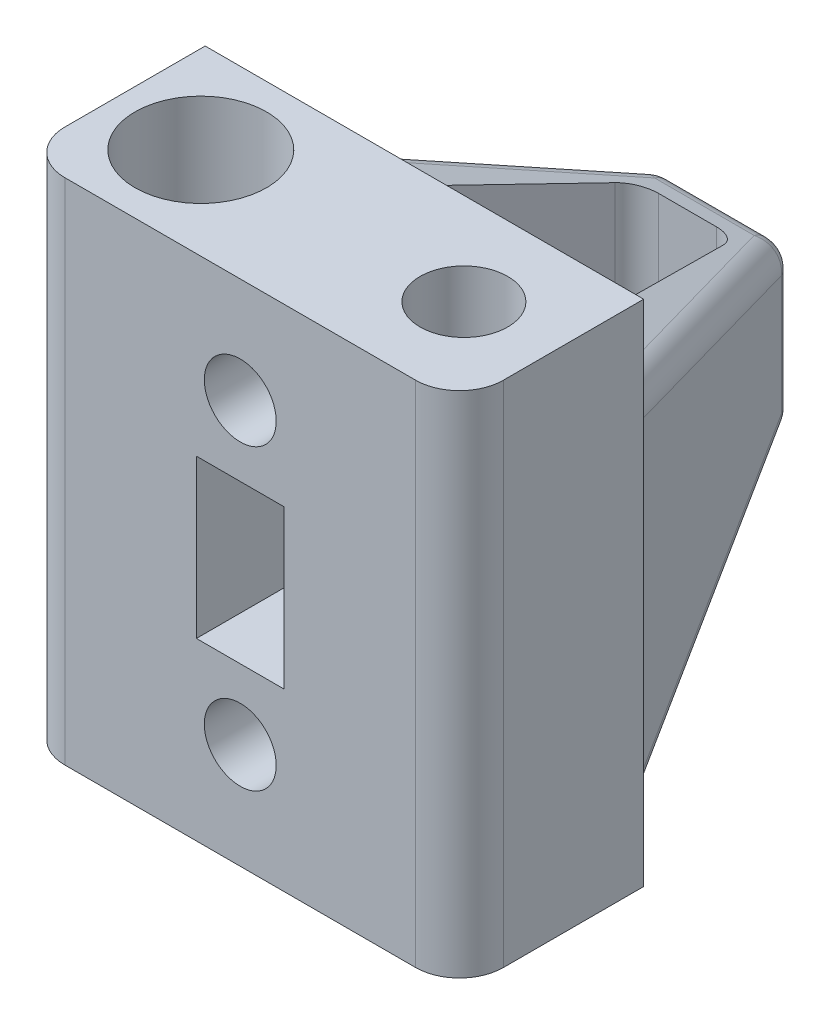
SolidWorks part; units mm, degrees
ref_plane "Front Plane" through (0, 0, 0) normal (0, 0, 1) x (1, 0, 0)
ref_plane "Top Plane" through (0, 0, 0) normal (0, 1, 0) x (1, 0, 0)
ref_plane "Right Plane" through (0, 0, 0) normal (1, 0, 0) x (0, 0, -1)
sketch "Sketch1" plane through (0, 0, 0) normal (0, 1, 0) x (1, 0, 0)
  line L1 (-25, 10.5) -> (25, 10.5)
  line L2 (-25, 10.5) -> (-25, -10.5)
  line L3 (-25, -10.5) -> (25, -10.5)
  line L4 (25, 10.5) -> (25, -10.5)
  line L5 (-25, 10.5) -> (25, -10.5) construction
  line L6 (-25, -10.5) -> (25, 10.5) construction
  point P0 (0, 0)
  dimension "D1" = 21
  dimension "D2" = 50
extrude "Boss-Extrude1" add sketch "Sketch1" along normal blind 58
sketch "Sketch3" plane through (0, 58, 0) normal (0, 1, 0) x (1, 0, 0)
  line L0 (-15, 0) -> (15, 0) construction
  circle A0 centre (-15, 0) radius 7.5
  dimension "D1" = 15
  dimension "D2" = 30
extrude "Cut-Extrude1" cut sketch "Sketch3" against normal blind 24 contours A0
sketch "Sketch4" plane through (0, 58, 0) normal (0, 1, 0) x (1, 0, 0)
  line L0 (-15, 0) -> (15, 0) construction
  circle A0 centre (15, 0) radius 5
  dimension "D1" = 10
extrude "Cut-Extrude2" cut sketch "Sketch4" against normal up to next
sketch "Sketch5" plane through (0, 0, 0) normal (0, -1, 0) x (1, 0, 0)
  circle A1 centre (-15, 0) radius 7.5
  circle A2 centre (-15, 0) radius 7.5
  dimension "D1" = 0
extrude "Cut-Extrude3" cut sketch "Sketch5" against normal blind 24
sketch "Sketch6" plane through (0, 0, 0) normal (0, -1, 0) x (1, 0, 0)
  circle A0 centre (-15, 0) radius 4.5
extrude "Cut-Extrude4" cut sketch "Sketch6" against normal up to next
sketch "Sketch7" plane through (0, 0, 10.5) normal (0, 0, 1) x (1, 0, 0)
  line L0 (0, 58) -> (0, 0) construction
  line L1 (-25, 58) -> (25, 58) construction
  line L2 (-25, 0) -> (25, 0) construction
  line L3 (-25, 29) -> (25, 29) construction
  line L4 (-25, 58) -> (-25, 0) construction
  line L5 (25, 58) -> (25, 0) construction
  circle A1 centre (0, 46) radius 4.1
  circle A2 centre (0, 12) radius 4.1
  point P24 (0, 12)
  dimension "D1" = 8.2
  dimension "D2" = 12
sketch "Sketch8" plane through (0, 0, 10.5) normal (0, 0, 1) x (1, 0, 0)
  line L0 (-25, 29) -> (25, 29) construction
  line L1 (-25, 58) -> (-25, 0) construction
  line L2 (25, 58) -> (25, 0) construction
  line L3 (0, 58) -> (0, 0) construction
  line L4 (-25, 58) -> (25, 58) construction
  line L6 (-5, 20) -> (5, 20)
  line L7 (-5, 20) -> (-5, 38)
  line L8 (-5, 38) -> (5, 38)
  line L9 (5, 20) -> (5, 38)
  line L10 (-5, 20) -> (5, 38) construction
  line L11 (-5, 38) -> (5, 20) construction
  point P11 (0, 29)
  dimension "D1" = 18
  dimension "D2" = 10
extrude "Cut-Extrude5" cut sketch "Sketch8" against normal up to next
sketch "Sketch10" plane through (0, 0, -10.5) normal (0, 0, -1) x (-1, 0, 0)
  line L0 (-25, 29) -> (25, 29) construction
  line L1 (-25, 58) -> (-25, 0) construction
  line L2 (25, 58) -> (25, 0) construction
  line L3 (0, 58) -> (0, 0) construction
  line L4 (-25, 58) -> (25, 58) construction
ref_plane "Plane1" through (0, 29, 0) normal (0, 1, 0) x (0, 0, -1)
sketch "Sketch11" plane through (0, 29, 0) normal (0, 1, 0) x (0, 0, -1)
  line L0 (10.5, 0) -> (63.0219, 0) construction
  line L1 (10.5, -25) -> (10.5, 25) construction
  line L2 (40.5, 5.5) -> (40.5, -5.5)
  line L3 (44.5, 7.5) -> (44.5, -7.5)
  line L4 (44.5, -7.5) -> (10.5, -25)
  line L5 (44.5, 7.5) -> (10.5, 25)
  line L6 (10.5, -25) -> (10.5, -15)
  line L7 (10.5, 25) -> (10.5, 15)
  line L8 (10.5, -15) -> (40.5, -5.5)
  line L9 (10.5, 15) -> (40.5, 5.5)
  point P8 (40.5, 0)
  point P11 (44.5, 0)
  dimension "D1" = 11
  dimension "D2" = 30
  dimension "D3" = 4
  dimension "D4" = 15
  dimension "D5" = 15
extrude "Boss-Extrude3" add sketch "Sketch11" along normal mid plane 40
ref_plane "Plane2" through (0, 0, 0) normal (-1, 0, 0) x (0, 0, 1)
sketch "Sketch12" plane through (0, 0, 0) normal (-1, 0, 0) x (0, 0, 1)
  line L0 (-10.5, 29) -> (-59.7607, 29) construction
  line L1 (-10.5, 58) -> (-10.5, 0) construction
  line L2 (-44.5, 20) -> (-44.5, 38) construction
  line L3 (-44.5, 49) -> (-44.5, 9) construction
  line L4 (-44.5, 38) -> (-10.5, 49)
  line L5 (-44.5, 20) -> (-10.5, 9)
  line L6 (-10.5, 49) -> (-44.5, 49)
  line L7 (-10.5, 9) -> (-44.5, 9)
  line L8 (-44.5, 49) -> (-44.5, 38)
  line L9 (-44.5, 9) -> (-44.5, 20)
  point P9 (-44.5, 29)
  dimension "D1" = 18
extrude "Cut-Extrude6" cut sketch "Sketch12" against normal mid plane 75
sketch "Sketch13" plane through (0, 0, -44.5) normal (0, 0, -1) x (-1, 0, 0)
  line L0 (-25, 29) -> (25, 29) construction
  circle A0 centre (0, 29) radius 2
  dimension "D1" = 4
extrude "Cut-Extrude7" cut sketch "Sketch13" against normal up to next
extrude "Cut-Extrude8" cut sketch "Sketch7" against normal blind 15
fillet "Fillet1" radius 5 2 edges at (25, 29, 10.5) (-25, 29, 10.5)
fillet "Fillet2" radius 3 8 edges at (7.5, 29, -44.5) (0, 38, -44.5) (-7.5, 29, -44.5) (0, 20, -44.5) (16.25, 14.5, -27.5) (16.25, 43.5, -27.5) (-16.25, 43.5, -27.5) (-16.25, 14.5, -27.5)
fillet "Fillet3" radius 3 2 edges at (-5.5, 29, -40.5) (5.5, 29, -40.5)
fillet "Fillet4" radius 3 2 edges at (-15, 29, -10.5) (15, 29, -10.5)
